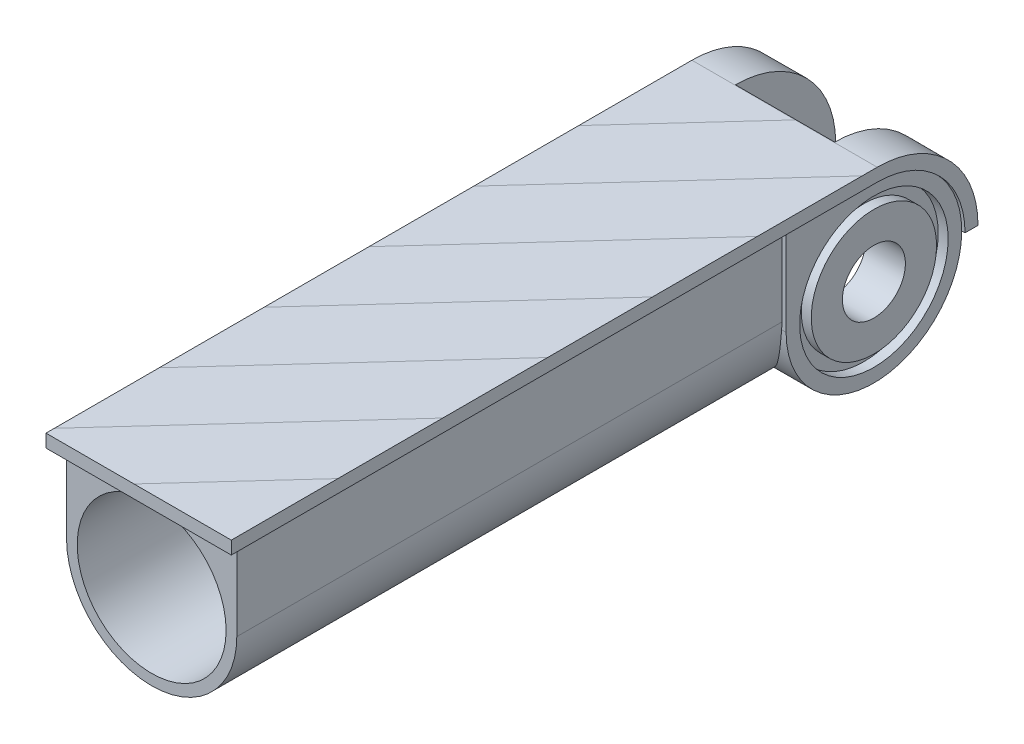
SolidWorks part; units mm, degrees
ref_plane "Front Plane" through (0, 0, 0) normal (0, 0, 1) x (1, 0, 0)
ref_plane "Top Plane" through (0, 0, 0) normal (0, 1, 0) x (1, 0, 0)
ref_plane "Right Plane" through (0, 0, 0) normal (1, 0, 0) x (0, 0, -1)
sketch "Sketch1" plane through (0, 0, 0) normal (0, 0, 1) x (1, 0, 0)
  line L0 (-8.7155, 8.2804) -> (8.7155, 8.2804)
  line L1 (8.7155, 8.2804) -> (8.7155, 0)
  line L2 (-8.7155, 0) -> (-8.7155, 8.2804)
  arc A0 (8.7155, 0) -> (-8.7155, 0) centre (0, 0) cw
  dimension "D1" = 17.4309
  dimension "D2" = 8.2804
extrude "Extrude1" add sketch "Sketch1" along normal blind 55.7945
sketch "Sketch2" plane through (0, 0, 55.7945) normal (0, 0, 1) x (1, 0, 0)
  circle A0 centre (0, 0) radius 7.62
  dimension "D1" = 15.24
sketch "Sketch6" plane through (0, 0, 0) normal (1, 0, 0) x (0, 0, -1)
  line L0 (0, 8.2804) -> (8.9889, 8.2804)
  line L1 (0, 8.2804) -> (0, -0.7085)
  arc A0 (8.9889, 8.2804) -> (0, -0.7085) centre (8.9889, -0.7085) cw
extrude "Extrude6" add sketch "Sketch6" along normal mid plane 18.2893
sketch "Sketch7" plane through (0, 0, 0) normal (0, 0, -1) x (-1, 0, 0)
  line L1 (8.6866, -0.7085) -> (-8.6866, -0.7085)
  line L2 (8.6866, -0.7085) -> (-8.6866, -0.7085)
  arc A1 (-8.6866, -0.7085) -> (8.6866, -0.7085) centre (0, 0) ccw
  arc A2 (-8.6866, -0.7085) -> (8.6866, -0.7085) centre (0, 0) ccw
  dimension "D1" = 0
extrude "Extrude7" add sketch "Sketch7" along normal up to surface up to face at (0, -1.329, -6.6131)
sketch "Sketch8" plane through (0, 0, 0) normal (1, 0, 0) x (0, 0, -1)
  line L0 (8.9889, 8.2804) -> (0, 8.2804) construction
  line L1 (-55.7945, 8.2804) -> (0, 8.2804) construction
  line L2 (8.9889, 8.2804) -> (0, 8.2804)
  line L3 (-57.1255, 8.2804) -> (0, 8.2804)
  arc A0 (0, -0.7085) -> (8.9889, 8.2804) centre (8.9889, -0.7085) ccw construction
  arc A1 (17.9777, -0.7085) -> (8.9889, 8.2804) centre (8.9889, -0.7085) ccw
extrude "Extrude-Thin1" add sketch "Sketch8" along normal mid plane 18.9675 thin
sketch "Sketch9" plane through (9.1446, 0, 0) normal (1, 0, 0) x (0, 0, -1)
  circle A0 centre (8.9889, -0.7085) radius 7.6019
  circle A1 centre (8.9889, -0.7085) radius 6.4146
extrude "Extrude8" cut sketch "Sketch9" against normal blind 1.016
sketch "Sketch10" plane through (9.1446, 0, 0) normal (1, 0, 0) x (0, 0, -1)
  circle A0 centre (8.9889, -0.7085) radius 3.2245
  dimension "D1" = 6.4491
extrude "Extrude9" cut sketch "Sketch10" against normal through all
mirror "Mirror1" about plane through (0, 0, 0) normal (1, 0, 0) of "Extrude8"
extrude "Extrude11" cut sketch "Sketch2" against normal blind 55.88
sketch "Sketch12" plane through (0, 0, 0) normal (1, 0, 0) x (0, 0, -1)
  circle A0 centre (8.9889, -0.7085) radius 9.0168
extrude "Extrude12" cut sketch "Sketch12" against normal mid plane 10.16
sketch "Sketch13" plane through (0, 0, 0) normal (0, 1, 0) x (1, 0, 0)
  line L3 (9.4838, 19.305) -> (-9.4838, 19.305) construction
  line L4 (-5.08, 0.0855) -> (-5.08, 18.0056) construction
  line L8 (5.08, 19.305) -> (-5.08, 19.305)
  line L9 (5.08, 0) -> (5.08, 19.305)
  line L10 (-5.08, 0) -> (5.08, 0)
  line L11 (-5.08, 19.305) -> (-5.08, 0)
extrude "Extrude13" cut sketch "Sketch13" against normal through all
sketch "Sketch16" plane through (0, 0, 0) normal (0, 1, 0) x (1, 0, 0)
  line L0 (5.08, 17.9777) -> (5.08, 0.0855) construction
  line L1 (-5.08, 19.2806) -> (5.08, 19.2806)
  line L2 (-5.08, 19.2806) -> (-5.08, 9.0316)
  line L3 (-5.08, 9.0316) -> (5.08, 9.0316)
  line L4 (5.08, 19.2806) -> (5.08, 9.0316)
extrude "Extrude16" cut sketch "Sketch16" along normal through all
sketch "Sketch17" plane through (0, 9.6076, 0) normal (0, 1, 0) x (1, 0, 0)
  line L0 (1.1358, 9.0316) -> (-9.4838, -2.6032)
  line L1 (-5.08, 9.0316) -> (5.08, 9.0316) construction
  line L2 (-9.4838, -57.1255) -> (-9.4838, 8.9889) construction
  line L3 (-9.4838, -2.6032) -> (-9.4838, -13.3358)
  line L4 (-9.4838, -13.3358) -> (9.4838, 7.4452)
  line L5 (9.4838, -57.1255) -> (9.4838, 8.9889) construction
  line L6 (9.4838, 7.4452) -> (9.4838, -3.2873)
  line L7 (9.4838, -3.2873) -> (-9.4838, -24.0683)
  line L8 (-9.4838, -24.0683) -> (-9.4838, -34.8008)
  line L9 (-9.4838, -34.8008) -> (9.4838, -14.0198)
  line L10 (9.4838, -14.0198) -> (9.4838, -24.7524)
  line L11 (9.4838, -24.7524) -> (-9.4838, -45.5334)
  line L12 (-9.4838, -45.5334) -> (-9.4838, -56.2659)
  line L13 (-9.4838, -56.2659) -> (9.4838, -35.4849)
  line L14 (9.4838, -35.4849) -> (9.4838, -46.2174)
  line L15 (9.4838, -46.2174) -> (-0.4724, -57.1255)
  line L16 (9.4838, -57.1255) -> (-9.4838, -57.1255) construction
split line "Split Line1"
